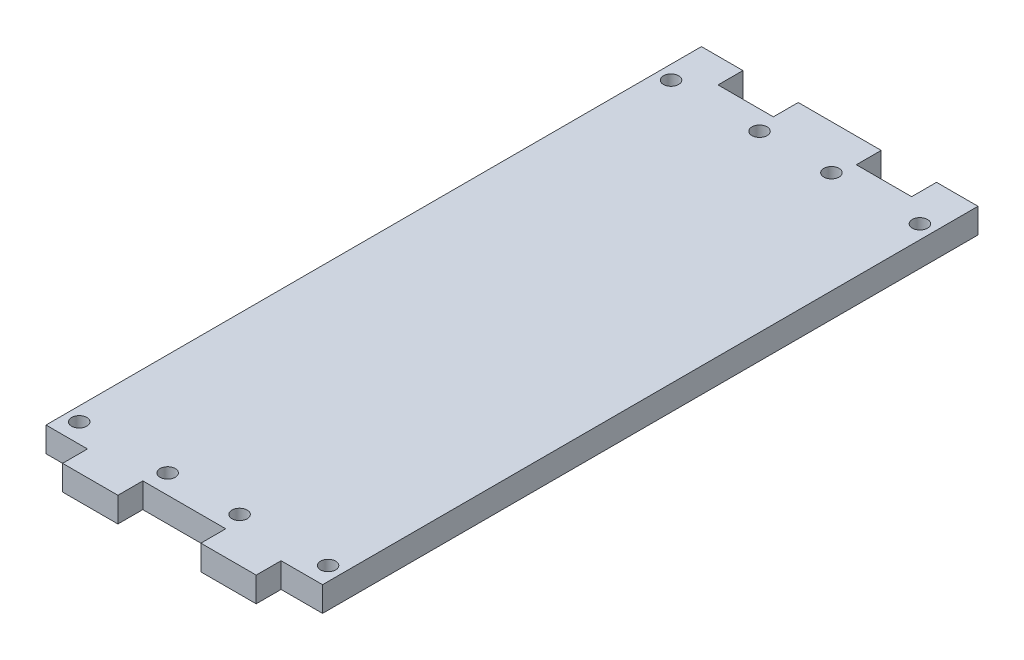
SolidWorks part; units mm, degrees
ref_plane "Front Plane" through (0, 0, 0) normal (0, 0, 1) x (1, 0, 0)
ref_plane "Top Plane" through (0, 0, 0) normal (0, 1, 0) x (1, 0, 0)
ref_plane "Right Plane" through (0, 0, 0) normal (1, 0, 0) x (0, 0, -1)
sketch "Sketch1" plane through (0, 0, 0) normal (0, 1, 0) x (1, 0, 0)
  line L0 (0, 118.5) -> (0, -118.5) construction
  line L1 (-50, 118.5) -> (50, 118.5)
  line L2 (-50, 118.5) -> (-50, -118.5)
  line L3 (-50, -118.5) -> (50, -118.5)
  line L4 (50, 118.5) -> (50, -118.5)
  line L5 (-50, 118.5) -> (50, -118.5) construction
  line L6 (-50, -118.5) -> (50, 118.5) construction
  line L7 (-35, -118.5) -> (-15, -118.5)
  line L8 (-35, -118.5) -> (-35, -127.5)
  line L9 (-35, -127.5) -> (-15, -127.5)
  line L10 (-15, -118.5) -> (-15, -127.5)
  line L11 (15, -118.5) -> (15, -127.5)
  line L12 (35, -127.5) -> (15, -127.5)
  line L13 (35, -118.5) -> (35, -127.5)
  line L14 (35, -118.5) -> (15, -118.5)
  line L15 (15, 118.5) -> (15, 109.5)
  line L16 (-35, 118.5) -> (-15, 118.5)
  line L17 (-35, 118.5) -> (-35, 109.5)
  line L18 (-35, 109.5) -> (-15, 109.5)
  line L19 (-15, 118.5) -> (-15, 109.5)
  line L20 (35, 109.5) -> (15, 109.5)
  line L21 (35, 118.5) -> (35, 109.5)
  line L22 (35, 118.5) -> (15, 118.5)
  point P0 (0, 0)
  dimension "D1" = 237
  dimension "D2" = 100
  dimension "D3" = 9
  dimension "D4" = 15
  dimension "D5" = 20
  dimension "D6" = 9
extrude "Boss-Extrude1" add sketch "Sketch1" along normal blind 9 contours L13 L3 L11 L12 | L21 L1 L15 L20 | L19 L1 L17 L18 | L9 L10 L7 L8
sketch "Sketch2" plane through (0, 9, 0) normal (0, 1, 0) x (1, 0, 0)
  line L0 (-50, -118.5) -> (-35, -118.5) construction
  line L1 (-50, 118.5) -> (-50, -118.5) construction
  line L2 (0, 118.5) -> (0, -118.5) construction
  line L3 (-15, 118.5) -> (15, 118.5) construction
  line L4 (-15, -118.5) -> (15, -118.5) construction
  line L5 (-50, 0) -> (50, 0) construction
  line L6 (50, 118.5) -> (50, -118.5) construction
  line L7 (-50, -4.5) -> (50, -4.5) construction
  circle A0 centre (-45, -111.5) radius 2.75
  circle A1 centre (-13, -111.5) radius 2.75
  circle A2 centre (13, -111.5) radius 2.75
  circle A3 centre (45, -111.5) radius 2.75
  circle A4 centre (-45, 102.5) radius 2.75
  circle A5 centre (-13, 102.5) radius 2.75
  circle A6 centre (13, 102.5) radius 2.75
  circle A7 centre (45, 102.5) radius 2.75
  dimension "D1" = 7
  dimension "D2" = 5.5
  dimension "D4" = 32
  dimension "D5" = 5.5
  dimension "D3" = 5
  dimension "D6" = 4.5
extrude "Cut-Extrude1" cut sketch "Sketch2" against normal blind 10
